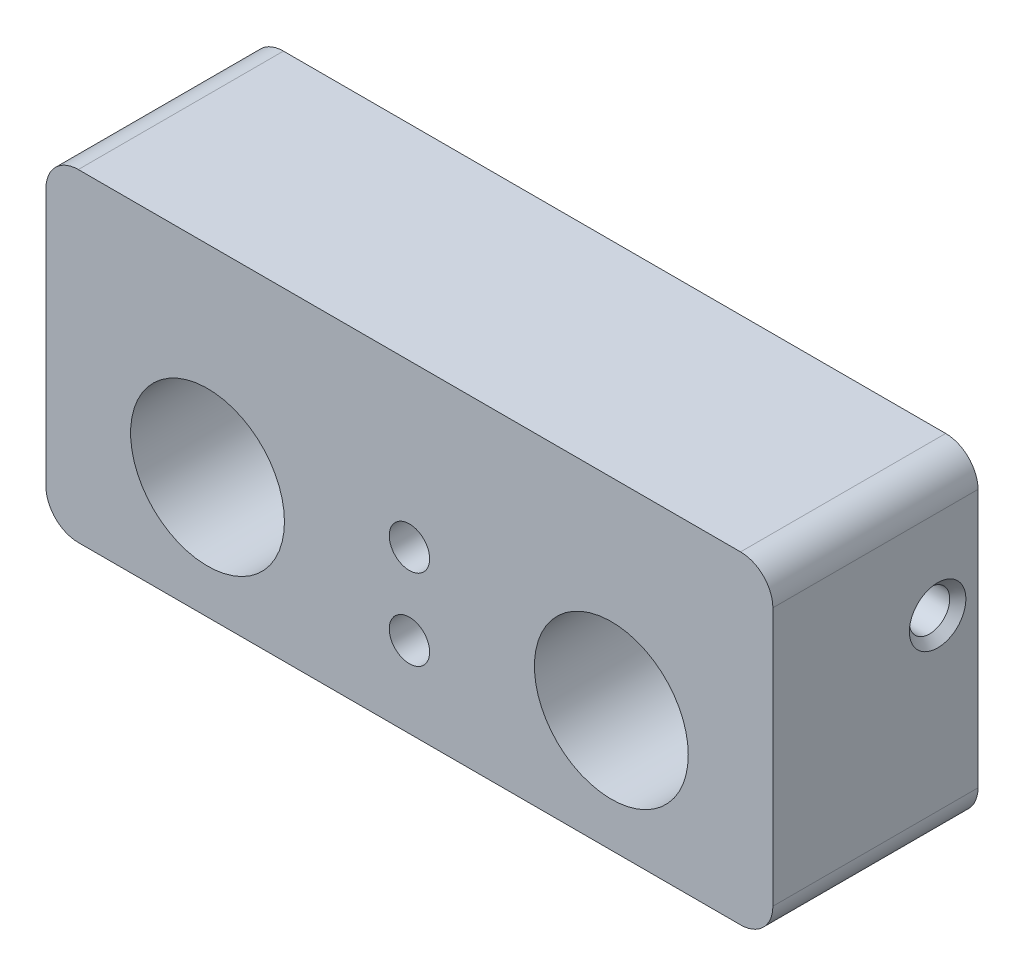
SolidWorks part; units mm, degrees
ref_plane "Front Plane" through (0, 0, 0) normal (0, 0, 1) x (1, 0, 0)
ref_plane "Top Plane" through (0, 0, 0) normal (0, 1, 0) x (1, 0, 0)
ref_plane "Right Plane" through (0, 0, 0) normal (1, 0, 0) x (0, 0, -1)
sketch "Sketch1" plane through (0, 0, 0) normal (0, 0, 1) x (1, 0, 0)
  line L1 (-16.681, 3.7155) -> (28.319, 3.7155)
  line L2 (-16.681, 3.7155) -> (-16.681, -16.2845)
  line L3 (-16.681, -16.2845) -> (28.319, -16.2845)
  line L4 (28.319, 3.7155) -> (28.319, -16.2845)
  circle A0 centre (-6.681, -8.7845) radius 4.7625
  circle A1 centre (18.319, -8.7845) radius 4.7625
  dimension "D3" = 9.525
  dimension "D4" = 9.525
  dimension "D1" = 45
  dimension "D2" = 20
  dimension "D5" = 10
  dimension "D6" = 10
  dimension "D7" = 7.5
  dimension "D8" = 0
  dimension "D9" = 12.5
  dimension "D10" = 25
extrude "Boss-Extrude1" add sketch "Sketch1" along normal blind 12.7
sketch "Sketch2" plane through (0, 0, 12.7) normal (0, 0, 1) x (1, 0, 0)
  line L0 (28.319, -16.2845) -> (28.319, 3.7155) construction
  line L1 (-16.681, 3.7155) -> (28.319, 3.7155)
  line L2 (-16.681, 3.7155) -> (-16.681, -1.2845)
  line L3 (-16.681, -1.2845) -> (28.319, -1.2845)
  line L4 (28.319, 3.7155) -> (28.319, -1.2845)
  line L5 (-16.681, -16.2845) -> (28.319, -16.2845) construction
  circle A0 centre (5.819, -11.2845) radius 1.1148
  circle A1 centre (5.819, -6.2845) radius 0.924
  dimension "D1" = 5
  dimension "D2" = 5
  dimension "D3" = 5
hole_wizard "Tap Drill for M3x0.5 Tap1" positions "Sketch3" profile "Sketch4" hole size "M3x0.5" standard "ANSI Metric"
sketch "Sketch3" plane through (0, 0, 12.7) normal (0, 0, 1) x (1, 0, 0)
  point P0 (5.819, -6.2845)
  point P3 (5.819, -11.2845)
sketch "Sketch4" plane through (5.819, -6.2845, 12.7) normal (1, 0, 0) x (0, -1, 0)
  line L0 (0, 0) -> (0, 10.7511)
  line L1 (0, 10.7511) -> (1.25, 10)
  line L2 (1.25, 10) -> (1.25, 0)
  line L5 (1.25, 0) -> (0, 0)
  line L10 (0, 10.7511) -> (-1.25, 10) construction
  line L11 (0, -6.35) -> (0, 107.95) construction
  dimension "Hole Dia." = 2.5
  dimension "Hole Depth" = 10
  dimension "Drill Angle" = 118
fillet "Fillet1" radius 2 4 edges at (28.319, -16.2845, 6.35) (28.319, 3.7155, 6.35) (-16.681, 3.7155, 6.35) (-16.681, -16.2845, 6.35)
sketch "Sketch5" plane through (-16.681, 0, 0) normal (-1, 0, 0) x (0, 0, 1)
  line L1 (0, 3.7155) -> (12.7, 3.7155) construction
  line L2 (0, 1.7155) -> (0, -14.2845) construction
  circle A0 centre (2.5, -3.7845) radius 1
  dimension "D3" = 2
  dimension "D1" = 7.5
  dimension "D2" = 2.5
hole_wizard "Tap Drill for M3x0.5 Tap2" positions "Sketch6" profile "Sketch8" hole size "M3x0.5" standard "ANSI Metric"
sketch "Sketch6" plane through (-16.681, 0, 0) normal (-1, 0, 0) x (0, 0, 1)
  point P0 (2.5, -3.7845)
sketch "Sketch8" plane through (-16.681, -3.7845, 2.5) normal (0, 1, 0) x (0, 0, 1)
  line L0 (0, 0) -> (0, 5.7511)
  line L1 (0, 5.7511) -> (1.25, 5)
  line L2 (1.25, 5) -> (1.25, 0)
  line L5 (1.25, 0) -> (0, 0)
  line L10 (0, 5.7511) -> (-1.25, 5) construction
  line L11 (0, -6.35) -> (0, 107.95) construction
  dimension "Hole Dia." = 2.5
  dimension "Hole Depth" = 5
  dimension "Drill Angle" = 118
ref_plane "Plane1" through (5.819, 0, 0) normal (1, 0, 0) x (0, 0, -1)
mirror "Mirror3" about plane through (5.819, 0, 0) normal (1, 0, 0) of "Tap Drill for M3x0.5 Tap2"
chamfer "Chamfer1" distance 0.5 angle 45 2 edges at (-16.681, -3.7845, 3.75) (28.319, -3.7845, 1.25)
equation "\"bearing_OD\"=9.525"
equation "\"D3@Sketch1\"=\"bearing_OD\""
equation "\"D4@Sketch1\"=\"bearing_OD\""
equation "\"bearing_width\"=12.7"
equation "\"D1@Boss-Extrude1\"=\"bearing_width\""
